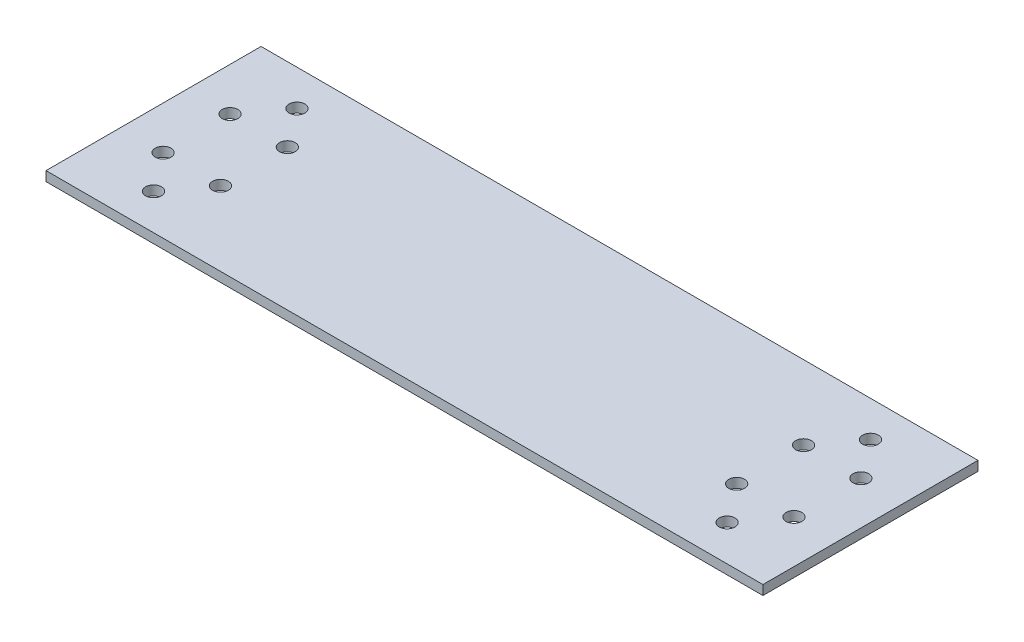
SolidWorks part; units mm, degrees
ref_plane "前视基准面" through (0, 0, 0) normal (0, 0, 1) x (1, 0, 0)
ref_plane "上视基准面" through (0, 0, 0) normal (0, 1, 0) x (1, 0, 0)
ref_plane "右视基准面" through (0, 0, 0) normal (1, 0, 0) x (0, 0, -1)
sketch "草图1" plane through (0, 0, 0) normal (0, 1, 0) x (1, 0, 0)
  line L1 (-75, -22.5) -> (75, -22.5)
  line L2 (-75, -22.5) -> (-75, 22.5)
  line L3 (-75, 22.5) -> (75, 22.5)
  line L4 (75, -22.5) -> (75, 22.5)
  line L5 (-75, -22.5) -> (75, 22.5) construction
  line L6 (-75, 22.5) -> (75, -22.5) construction
  point P0 (0, 0)
  dimension "D1" = 45
  dimension "D2" = 150
extrude "凸台-拉伸1" add sketch "草图1" along normal blind 2
sketch "草图2" plane through (0, 2, 0) normal (0, 1, 0) x (1, 0, 0)
  line L1 (-60, -11) -> (60, -11) construction
  line L2 (-60, -11) -> (-60, 11) construction
  line L3 (-60, 11) -> (60, 11) construction
  line L4 (60, -11) -> (60, 11) construction
  line L5 (-60, -11) -> (60, 11) construction
  line L6 (-60, 11) -> (60, -11) construction
  line L12 (-66, 7) -> (-54, 7) construction
  line L14 (-66, 7) -> (-66, 15) construction
  line L15 (-66, 15) -> (-54, 15) construction
  line L16 (-54, 7) -> (-54, 15) construction
  line L17 (-66, 7) -> (-54, 15) construction
  line L18 (-66, 15) -> (-54, 7) construction
  circle A4 centre (-60, 15) radius 1.65
  circle A5 centre (-66, 7) radius 1.65
  circle A6 centre (-54, 7) radius 1.65
  point P0 (0, 0)
  point P14 (-60, 0)
  dimension "D5" = 3.3
  dimension "D1" = 12
  dimension "D2" = 8
  dimension "D3" = 15
  dimension "D4" = 120
extrude "切除-拉伸1" cut sketch "草图2" against normal up to next
mirror "镜向1" about plane through (0, 0, 0) normal (0, 0, 1) of "切除-拉伸1"
mirror "镜向2" about plane through (0, 0, 0) normal (1, 0, 0) of "镜向1", "切除-拉伸1"
